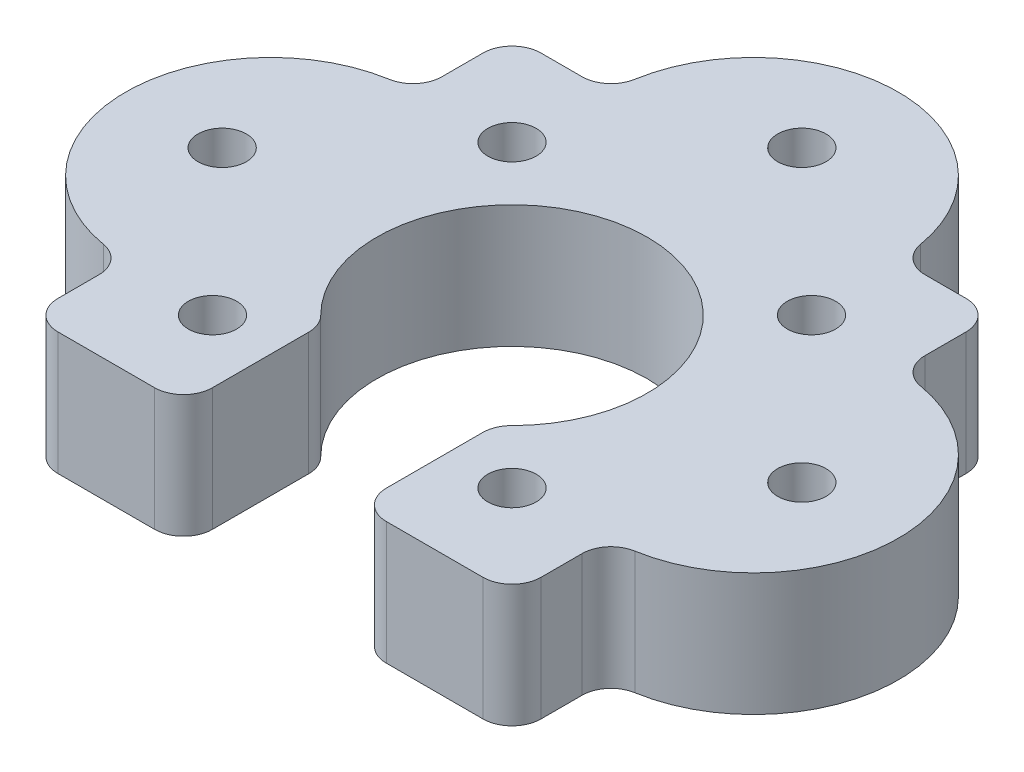
SolidWorks part; units mm, degrees
material "6061 Alloy"
ref_plane "Front Plane" through (0, 0, 0) normal (0, 0, 1) x (1, 0, 0)
ref_plane "Top Plane" through (0, 0, 0) normal (0, 1, 0) x (1, 0, 0)
ref_plane "Right Plane" through (0, 0, 0) normal (1, 0, 0) x (0, 0, -1)
sketch "Sketch1" plane through (0, 0, 0) normal (0, 1, 0) x (1, 0, 0)
  line L0 (-25, -25) -> (-9, -25)
  line L1 (-9, -25) -> (-9, -10.7238)
  line L3 (9, -10.7238) -> (9, -25)
  line L4 (9, -25) -> (25, -25)
  line L5 (25, -25) -> (25, 25)
  line L6 (25, 25) -> (-25, 25)
  line L7 (-25, 25) -> (-25, -25)
  line L8 (0, 0) -> (0, 15.5) construction
  line L9 (-15.5, 15.5) -> (15.5, 15.5) construction
  line L10 (-15.5, 15.5) -> (-15.5, -15.5) construction
  line L11 (-15.5, -15.5) -> (15.5, -15.5) construction
  line L12 (15.5, 15.5) -> (15.5, -15.5) construction
  circle A0 centre (-15.5, -15.5) radius 1.5 construction
  circle A1 centre (15.5, -15.5) radius 1.5 construction
  circle A2 centre (15.5, 15.5) radius 1.5 construction
  circle A3 centre (-15.5, 15.5) radius 1.5 construction
  arc A4 (9, -10.7238) -> (-9, -10.7238) centre (0, 0) ccw
  circle A5 centre (-30, 0) radius 1.5 construction
  arc A6 (-25, 15) -> (-25, -15) centre (-25, 0) ccw
  arc A9 (15, 25) -> (-15, 25) centre (0, 25) ccw
  circle A10 centre (0, 30) radius 1.5 construction
  arc A11 (25, -15) -> (25, 15) centre (25, 0) ccw
  circle A12 centre (30, 0) radius 1.5 construction
  point P25 (15.5, 0)
  point P26 (25, 0)
  point P39 (0, 0)
  dimension "D3" = 3
  dimension "D4" = 14
  dimension "D5" = 5
  dimension "D6" = 3
  dimension "D7" = 30
  dimension "D1" = 31
  dimension "D2" = 50
  dimension "D8" = 18
  dimension "D9" = 3
extrude "Boss-Extrude1" add sketch "Sketch1" against normal blind 12.7
hole_wizard "Tap Drill for M6x1.0 Tap1" positions "3DSketch1" profile "Sketch2" hole size "M6x1.0" standard "ANSI Metric" end condition through all
sketch3d "3DSketch1"
  point P0 (-15.5, 0, 15.5)
  point P2 (-15.5, 0, -15.5)
  point P4 (15.5, 0, -15.5)
  point P6 (15.5, 0, 15.5)
  point P10 (-30, 0, 0)
  point P27 (0, 0, -30)
  point P29 (30, 0, 0)
sketch "Sketch2" plane through (-15.5, 0, 15.5) normal (1, 0, 0) x (0, 0, 1)
  line L0 (0, 0) -> (0, 12.7)
  line L1 (0, 12.7) -> (2.5, 12.7)
  line L2 (2.5, 12.7) -> (2.5, 0)
  line L5 (2.5, 0) -> (0, 0)
  line L11 (0, -6.35) -> (0, 107.95) construction
  dimension "Thru Hole Dia." = 5
  dimension "Thru Hole Depth" = 12.7
fillet "Fillet1" radius 3 14 edges at (-9, -6.35, 25) (9, -6.35, 25) (9, -6.35, 10.7238) (-9, -6.35, 10.7238) (-25, -6.35, -15) (-25, -6.35, 15) (-25, -6.35, -25) (25, -6.35, -25) (25, -6.35, 25) (-25, -6.35, 25) (15, -6.35, -25) (-15, -6.35, -25) (25, -6.35, 15) (25, -6.35, -15)
